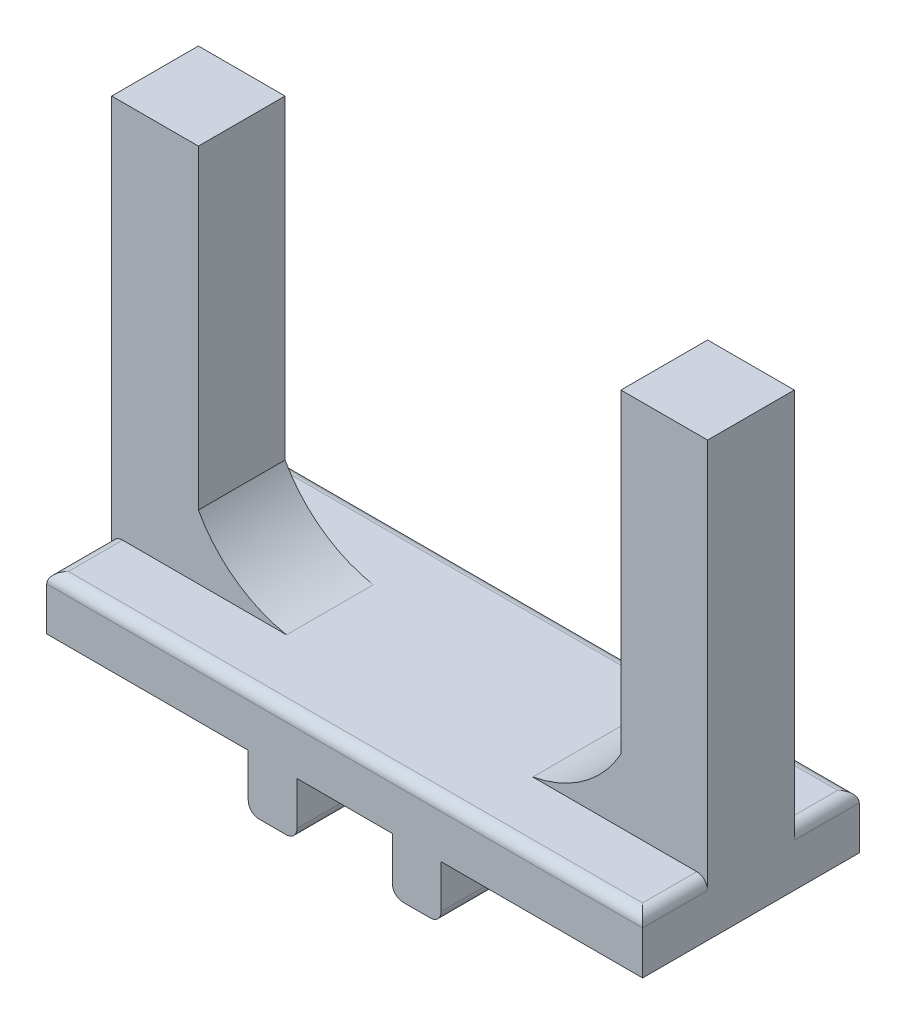
SolidWorks part; units mm, degrees
ref_plane "Front Plane" through (0, 0, 0) normal (0, 0, 1) x (1, 0, 0)
ref_plane "Top Plane" through (0, 0, 0) normal (0, 1, 0) x (1, 0, 0)
ref_plane "Right Plane" through (0, 0, 0) normal (1, 0, 0) x (0, 0, -1)
sketch "Sketch1" plane through (0, 0, 0) normal (0, 0, 1) x (1, 0, 0)
  line L0 (0, 0) -> (0, 35.9328) construction
  line L2 (-27.5, 2.5) -> (27.5, 2.5)
  line L3 (-27.5, 2.5) -> (-27.5, -2.5)
  line L4 (-27.5, -2.5) -> (27.5, -2.5)
  line L5 (27.5, 2.5) -> (27.5, -2.5)
  line L6 (-27.5, 2.5) -> (27.5, -2.5) construction
  line L7 (-27.5, -2.5) -> (27.5, 2.5) construction
  line L8 (-8.9, -2.5) -> (-4.4, -2.5)
  line L9 (-8.9, -2.5) -> (-8.9, -7.5)
  line L10 (-8.9, -7.5) -> (-4.4, -7.5)
  line L11 (-4.4, -2.5) -> (-4.4, -7.5)
  line L12 (4.4, -2.5) -> (8.9, -2.5)
  line L13 (4.4, -2.5) -> (4.4, -7.5)
  line L14 (4.4, -7.5) -> (8.9, -7.5)
  line L15 (8.9, -2.5) -> (8.9, -7.5)
  dimension "D1" = 5
  dimension "D2" = 55
  dimension "D3" = 5
  dimension "D4" = 4.5
  dimension "D5" = 5
  dimension "D6" = 4.5
  dimension "D7" = 8.8
  dimension "D8" = 4.4
extrude "Boss-Extrude2" add sketch "Sketch1" along normal blind 20 contours L5 L2 L3 L4 | L11 L4 L9 L10 | L15 L4 L13 L14
sketch "Sketch2" plane through (0, 2.5, 0) normal (0, 1, 0) x (1, 0, 0)
  line L0 (0, 0) -> (0, -20) construction
  line L1 (-27.5, 0) -> (27.5, 0) construction
  line L2 (-27.5, -20) -> (27.5, -20) construction
  line L3 (-27.5, -10) -> (27.5, -10) construction
  line L4 (-27.5, -20) -> (-27.5, 0) construction
  line L5 (27.5, -20) -> (27.5, 0) construction
  line L6 (27.5, -14) -> (19.5, -14)
  line L7 (-27.5, -6) -> (-19.5, -6)
  line L8 (-27.5, -6) -> (-27.5, -14)
  line L9 (-27.5, -14) -> (-19.5, -14)
  line L10 (-19.5, -6) -> (-19.5, -14)
  line L11 (-27.5, -6) -> (-19.5, -14) construction
  line L12 (-27.5, -14) -> (-19.5, -6) construction
  line L13 (19.5, -6) -> (19.5, -14)
  line L14 (27.5, -6) -> (19.5, -6)
  line L15 (27.5, -6) -> (27.5, -14)
  point P12 (-23.5, -10)
  dimension "D1" = 8
  dimension "D2" = 8
  dimension "D3" = 8
extrude "Boss-Extrude3" add sketch "Sketch2" along normal blind 35
fillet "Fillet1" radius 1 10 edges at (-4.4, -7.5, 10) (4.4, -7.5, 10) (8.9, -7.5, 10) (-8.9, -7.5, 10) (27.5, 2.5, 3) (27.5, 2.5, 17) (0, 2.5, 0) (0, 2.5, 20) (-27.5, 2.5, 3) (-27.5, 2.5, 17)
ref_plane "Plane1" through (0, 0, 10) normal (0, 0, 1) x (1, 0, 0)
sketch "Sketch9" plane through (0, 0, 10) normal (0, 0, 1) x (1, 0, 0)
  line L0 (-19.5, 8.4051) -> (-19.5, 2.5)
  line L1 (-19.5, 37.5) -> (-19.5, 2.5) construction
  line L2 (-26.5, 2.5) -> (-19.5, 2.5) construction
  line L3 (-19.5, 2.5) -> (-11.3641, 2.5)
  line L4 (-26.5, 2.5) -> (26.5, 2.5) construction
  arc A0 (-19.5, 8.4051) -> (-11.3641, 2.5) centre (-9.1583, 14.0965) ccw
extrude "Boss-Extrude4" add sketch "Sketch9" along normal blind 4 and the other way blind 4
mirror "Mirror1" about plane through (0, 0, 0) normal (1, 0, 0) of "Boss-Extrude4"
